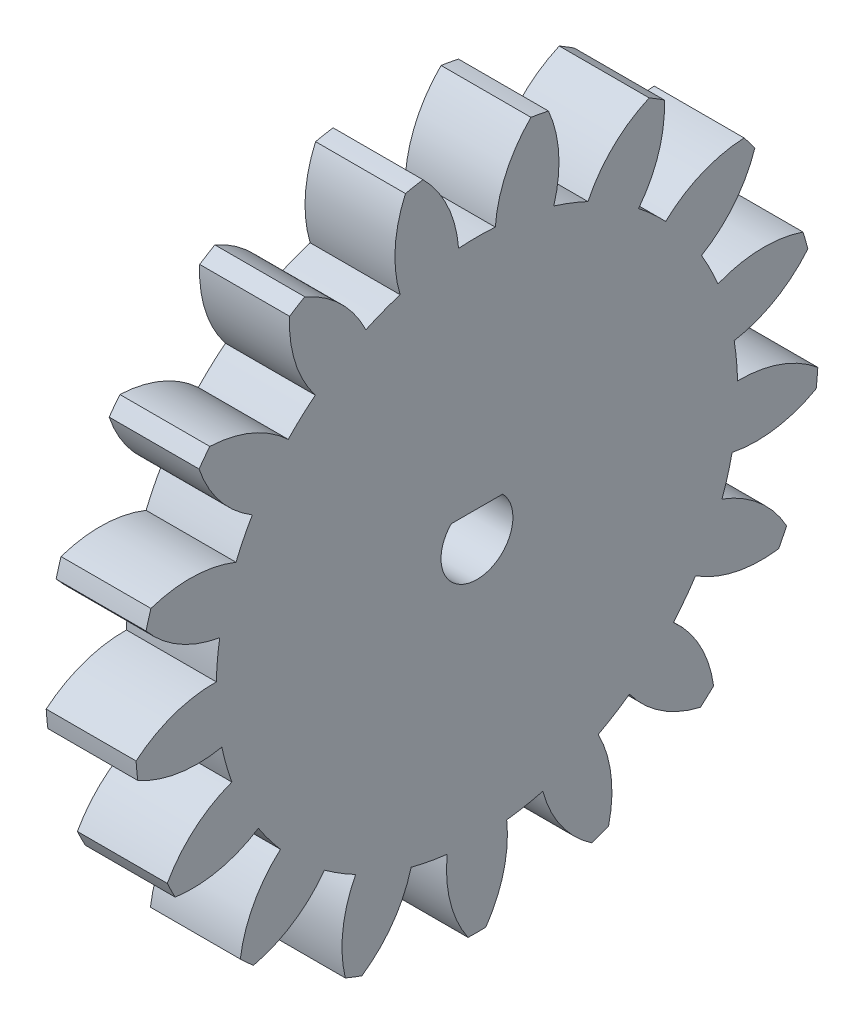
SolidWorks part; units mm, degrees
ref_plane "Plane1" through (0, 0, 0) normal (0, 0, 1) x (1, 0, 0)
ref_plane "Plane2" through (0, 0, 0) normal (0, 1, 0) x (1, 0, 0)
ref_plane "Plane3" through (0, 0, 0) normal (1, 0, 0) x (0, 0, -1)
sketch "HoldingSke" plane through (0, 0, 0) normal (0, 1, 0) x (1, 0, 0)
  line L0 (0, 0) -> (0.4782, -0.1462)
  line L1 (-15, 0) -> (100, 0) construction
  line L2 (0, 0) -> (-2.1039, 2.3779)
  line L3 (0, 0) -> (-11.863, 4.5341)
  line L4 (0, 0) -> (8.2586, 2.5249)
  line L5 (0, 0) -> (-46.8476, -17.4728)
  line L6 (0, 0) -> (-4.1448, -2.7965)
  line L7 (-2.1039, 2.3779) -> (8.6586, 51.2059)
  line L8 (-76.2, 54.61) -> (-75.5, 54.61)
  line L9 (-71.009, 38.7566) -> (-53.1078, 45.2721)
  line L10 (-76.2, 71.12) -> (104.1128, 71.12)
  line L11 (0, 0) -> (-5, 0)
  line L12 (-76.2, 101.6) -> (-76.133, 101.6)
  line L13 (24.9733, 27.94) -> (52.9518, 28.4284)
  line L14 (24.9733, 27.94) -> (24.9743, 27.94)
  line L15 (24.9733, 27.94) -> (100.4006, 29.5858)
  line L16 (-63.627, -2) -> (-12.827, -2)
  circle A0 centre (0, 0) radius 2
  circle A1 centre (0, 0) radius 14.499
  circle A2 centre (0, 0) radius 37.5
  circle A3 centre (0, 0) radius 2
  dimension "MHD" = 28.998
  dimension "Hub_dia" = 75
  dimension "Bore" = 4
  dimension "MBD" = 4
  dimension "Num_teeth" = 17
  dimension "Pitch" = 0.5
  dimension "Overall_len" = 50
  dimension "Show_teeth" = 17
  dimension "Thickness" = 5
  dimension "OAL" = 50.0001
  dimension "T_dim" = 0.7
  dimension "Ap" = 20
  dimension "H" = 19.05
  dimension "Pitch_radius" = 180.3128
  dimension "Width" = 5
  dimension "Backlash" = 0.067
  dimension "Addendum_fac" = 1
  dimension "Dedendum_fac" = 1.25
  dimension "Clearance_fac" = 0.25
  dimension "Dedendum_add" = 0.001
  dimension "Module" = 2
sketch "BasProSke" plane through (0, 0, 0) normal (0, 1, 0) x (1, 0, 0)
  line L0 (-10, 0) -> (60, 0) construction
  line L1 (0, 0) -> (0, 19)
  line L2 (0, 0) -> (5, 0)
  line L3 (5, 0) -> (5, 19)
  line L4 (5, 19) -> (0, 19)
  dimension "Thickness" = 5
  dimension "Diameter" = 38
revolve "Base-Revolve" add sketch "BasProSke" angle 360 about L0
sketch "TooCutSke" plane through (0, 0, 0) normal (1, 0, 0) x (0, 0, -1)
  line L1 (0, 0) -> (0, 107) construction
  line L2 (0, 0) -> (-1.6857, 16.9162) construction
  line L3 (0, 0) -> (-6.2247, 33.2991) construction
  line L4 (-1.6857, 16.9162) -> (-3.1123, 16.6495) construction
  arc A0 (1.0204, 14.4631) -> (-1.0204, 14.4631) centre (0, 0) ccw
  arc A1 (3.0261, 18.7832) -> (-3.0261, 18.7832) centre (0, 0) ccw
  circle A2 centre (0, 0) radius 17 construction
  circle A3 centre (0, 0) radius 15.9748 construction
  arc A4 (-1.0204, 14.4631) -> (-3.0261, 18.7832) centre (-7.8003, 13.9409) ccw
  arc A5 (3.0261, 18.7832) -> (1.0204, 14.4631) centre (7.8003, 13.9409) ccw
  dimension "Root_dia" = 28.998
  dimension "Overcut_dia" = 38.0508
  dimension "Pitch_dia" = 34
  dimension "Base_dia" = 31.9495
  dimension "Flank_rad" = 6.8
  dimension "Half_ang" = 10.588
  dimension "Half_CT" = 1.4513
extrude "ToothCut" cut sketch "TooCutSke" along normal through all
fillet "Breaks" [suppressed] radius 0.04
fillet "RootFillets" [suppressed] radius 0.501
pattern_circular "TeethCuts" count 17 every 21.176 about axis through (-10, 0, 0) along (1, 0, 0) of "ToothCut", "RootFillets", "Breaks"
sketch "HubNeaOneSke" plane through (0, 0, 0) normal (-1, 0, 0) x (0, 0, 1)
  circle A0 centre (0, 0) radius 14.499
  dimension "Diameter" = 28.998
extrude "HubNearOne" [suppressed] add sketch "HubNeaOneSke" along normal blind 45.0001
sketch "HubNeaBotSke" plane through (0, 0, 0) normal (-1, 0, 0) x (0, 0, 1)
  circle A0 centre (0, 0) radius 14.499
  dimension "Diameter" = 28.998
extrude "HubNearBoth" [suppressed] add sketch "HubNeaBotSke" along normal blind 22.5
ref_plane "FarPln" through (5, 0, 0) normal (1, 0, 0) x (0, 0, -1)
sketch "HubFarSke" plane through (5, 0, 0) normal (1, 0, 0) x (0, 0, -1)
  circle A0 centre (0, 0) radius 14.499
  dimension "Diameter" = 28.998
extrude "HubFar" [suppressed] add sketch "HubFarSke" along normal blind 22.5
sketch "BorSke" plane through (0, 0, 0) normal (1, 0, 0) x (0, 0, -1)
  circle A0 centre (0, 0) radius 2
  dimension "Diameter" = 4
extrude "Bore" cut sketch "BorSke" along normal mid plane 100.0001
sketch "KeySke" plane through (0, 0, 0) normal (1, 0, 0) x (0, 0, -1)
  line L0 (-0.8, 0) -> (-0.8, 2.7)
  line L1 (-0.8, 2.7) -> (0.8, 2.7)
  line L2 (0.8, 2.7) -> (0.8, 0)
  line L3 (0, 0) -> (0, 34) construction
  line L4 (-0.8, 0) -> (0.8, 0)
  dimension "Offset" = 2.7
  dimension "Width" = 1.6
extrude "Keyway" [suppressed] cut sketch "KeySke" along normal mid plane 100.0001
pattern_circular "Keyway2" [suppressed] count 2 every 90 about axis through (-10, 0, 0) along (1, 0, 0)
sketch "Sketch1" plane through (5, 0, 0) normal (1, 0, 0) x (0, 0, -1)
  line L0 (-1.4283, 1.4) -> (1.4283, 1.4)
  circle A0 centre (0, 0) radius 2 construction
  circle A1 centre (0, 0) radius 2
  dimension "D1" = 1.4
extrude "Boss-Extrude1" add sketch "Sketch1" against normal blind 5 contours L0 A1
equation "' \"Module@HoldingSke\" = 6.35"
equation "' \"Num_teeth@HoldingSke\" = 12"
equation "' \"Ap@HoldingSke\" =  20"
equation "' \"Ap@HoldingSke\" = 20"
equation "' \"Width@HoldingSke\" = 0.5 * 25.4"
equation "' \"Hub_dia@HoldingSke\"= 1 * 25.4"
equation "' \"Hub_dia@HoldingSke\" = 1 * 25.4"
equation "' \"Overall_len@HoldingSke\" = 1.0 * 25.4"
equation "' \"Bore@HoldingSke\" = 0.75 * 25.4"
equation "' \"T_dim@HoldingSke\" = 0.1 * 25.4"
equation "' \"Width@KeySke\" = 0.25 * 25.4"
equation "' \"Show_teeth@HoldingSke\" = 13"
equation "' \"Backlash@HoldingSke\" = 0.009 * 25.4"
equation "' \"Addendum_fac@HoldingSke\" = 1.0"
equation "' \"Dedendum_fac@HoldingSke\" = 1.25"
equation "' \"Dedendum_add@HoldingSke\" = 0.00005 * 25.4"
equation "' \"Clearance_fac@HoldingSke\" = 0.25"
equation "\"Pitch@HoldingSke\" = 1 / \"Module@HoldingSke\""
equation "\"Overcut_dia@TooCutSke\" = (\"Num_teeth@HoldingSke\" + 2 * \"Addendum_fac@HoldingSke\") / \"Pitch@HoldingSke\" + 0.002 * 25.4"
equation "\"Pitch_dia@TooCutSke\" = \"Num_teeth@HoldingSke\" / \"Pitch@HoldingSke\""
equation "\"Base_dia@TooCutSke\" = \"Num_teeth@HoldingSke\" / \"Pitch@HoldingSke\" * cos((\"Ap@HoldingSke\"  * 3.14159265 / 180))"
equation "\"Root_dia@TooCutSke\" = (\"Num_teeth@HoldingSke\" + 2) / \"Pitch@HoldingSke\" - 2 * (\"Addendum_fac@HoldingSke\" + \"Dedendum_fac@HoldingSke\") / \"Pitch@HoldingSke\" - \"Dedendum_add@HoldingSke\" * 2"
equation "\"Half_ang@TooCutSke\" = 180 / \"Num_teeth@HoldingSke\""
equation "\"Half_CT@TooCutSke\" = \"Num_teeth@HoldingSke\" / \"Pitch@HoldingSke\" * sin((3.14159265 / 2 / \"Num_teeth@HoldingSke\")) / 2 - 7 * \"Backlash@HoldingSke\" / 4"
equation "\"Flank_rad@TooCutSke\" = \"Num_teeth@HoldingSke\" / \"Pitch@HoldingSke\" / 5"
equation "\"Radius@RootFillets\" = \"Clearance_fac@HoldingSke\" / \"Pitch@HoldingSke\" + \"Dedendum_add@HoldingSke\""
equation "\"Break_rad@Breaks\" = 0.02 / \"Pitch@HoldingSke\""
equation "\"Thickness@HoldingSke\" = \"Width@HoldingSke\""
equation "\"OAL@HoldingSke\" = \"Thickness@HoldingSke\""
equation "\"MHD@HoldingSke\" = (\"Num_teeth@HoldingSke\" + 2) / \"Pitch@HoldingSke\" - 2 * (\"Addendum_fac@HoldingSke\" + \"Dedendum_fac@HoldingSke\")  / \"Pitch@HoldingSke\" - \"Dedendum_add@HoldingSke\" * 2"
equation "\"MBD@HoldingSke\" = (\"Num_teeth@HoldingSke\" + 2) / \"Pitch@HoldingSke\" - 2 * (\"Addendum_fac@HoldingSke\" + \"Dedendum_fac@HoldingSke\")  / \"Pitch@HoldingSke\" - \"Dedendum_add@HoldingSke\" * 2 - 0.002 * 25.4"
equation "\"MHD@HoldingSke\" = ((sgn( \"MHD@HoldingSke\" - \"Hub_dia@HoldingSke\" )-1)*( \"MHD@HoldingSke\" - \"Hub_dia@HoldingSke\" ))/-2+ \"Hub_dia@HoldingSke\""
equation "\"MBD@HoldingSke\" = ((sgn( \"MBD@HoldingSke\" - \"Bore@HoldingSke\" )-1)*( \"MBD@HoldingSke\" - \"Bore@HoldingSke\" ))/-2+ \"Bore@HoldingSke\""
equation "\"OAL@HoldingSke\" = ((sgn( \"OAL@HoldingSke\" - \"Overall_len@HoldingSke\" )+1)*( \"OAL@HoldingSke\" - \"Overall_len@HoldingSke\" ))/2 + \"Overall_len@HoldingSke\" + 0.000002 * 25.4"
equation "\"Num_teeth@TeethCuts\" = int( \"Show_teeth@HoldingSke\" ) + 1"
equation "\"Num_teeth@TeethCuts\" = ((sgn( \"Num_teeth@TeethCuts\" - \"Num_teeth@HoldingSke\" )-1)*( \"Num_teeth@TeethCuts\" - \"Num_teeth@HoldingSke\" ))/-2+ \"Num_teeth@HoldingSke\""
equation "\"Num_teeth@TeethCuts\" = ((sgn( \"Num_teeth@TeethCuts\" - 2.0)+1)*( \"Num_teeth@TeethCuts\" - 2.0))/2 +2.0"
equation "\"Angle@TeethCuts\" = 360.0 / \"Num_teeth@HoldingSke\""
equation "\"Diameter@BasProSke\" = (\"Num_teeth@HoldingSke\" + 2 * \"Addendum_fac@HoldingSke\") / \"Pitch@HoldingSke\""
equation "\"Thickness@BasProSke\"  = \"Thickness@HoldingSke\""
equation "' \"Fillet_rad@BasProSke\" =  \"Thickness@HoldingSke\" * 0.05"
equation "' \"Fillet_rad@BasProSke\" = \"Thickness@HoldingSke\" * 0.05"
equation "\"MHD@HoldingSke\" = ((sgn( \"MHD@HoldingSke\" - \"Root_dia@TooCutSke\" )-1)*( \"MHD@HoldingSke\" - \"Root_dia@TooCutSke\" ))/-2+ \"Root_dia@TooCutSke\""
equation "\"Diameter@HubNeaOneSke\" = \"MHD@HoldingSke\""
equation "\"Length@HubNearOne\" = \"OAL@HoldingSke\" - \"Thickness@BasProSke\""
equation "\"Diameter@HubNeaBotSke\" = \"MHD@HoldingSke\""
equation "\"Length@HubNearBoth\" = ( \"OAL@HoldingSke\" - \"Thickness@BasProSke\" ) / 2.0"
equation "\"Thickness@FarPln\" = \"Thickness@BasProSke\""
equation "\"Diameter@HubFarSke\" = \"MHD@HoldingSke\""
equation "\"Length@HubFar\" = ( \"OAL@HoldingSke\" - \"Thickness@BasProSke\" ) / 2.0"
equation "\"Diameter@BorSke\" = \"MBD@HoldingSke\""
equation "\"D1@Bore\" = \"OAL@HoldingSke\" * 2.0"
equation "\"D1@Keyway\" = \"OAL@HoldingSke\" * 2.0"
equation "\"Offset@KeySke\" = \"T_dim@HoldingSke\" + \"MBD@HoldingSke\" / 2.0"
